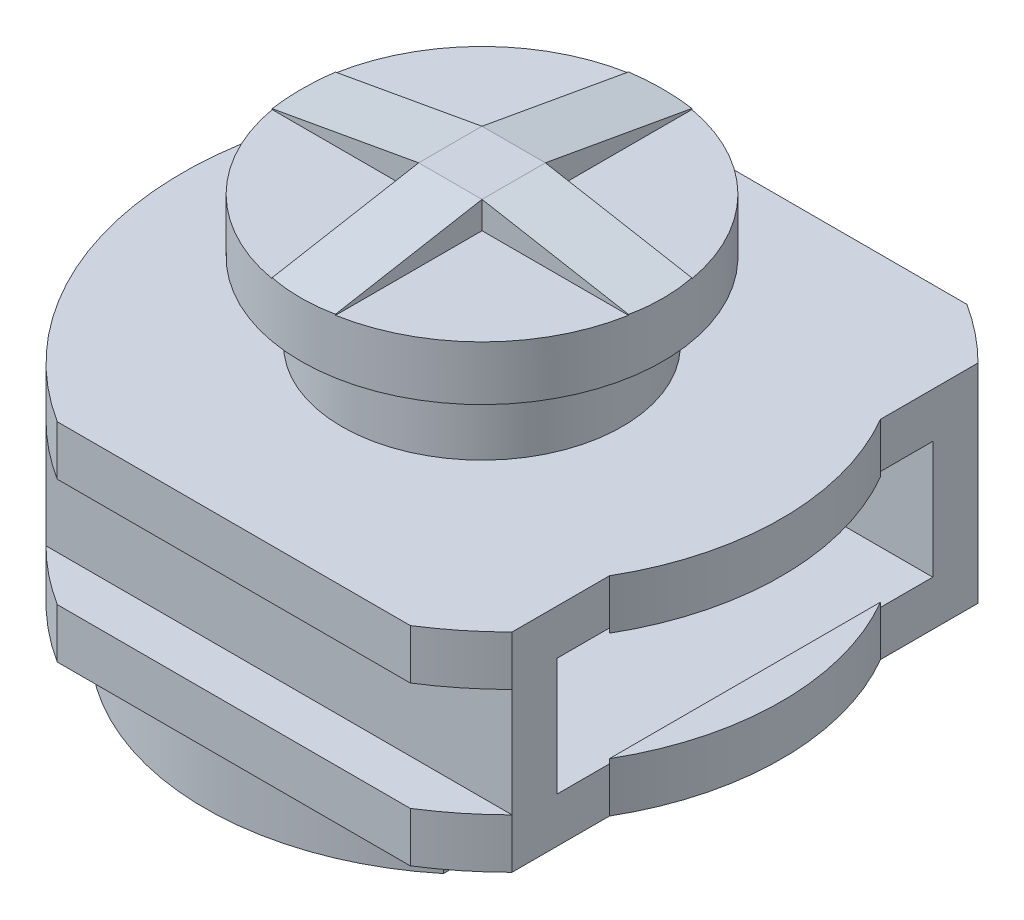
SolidWorks part; units mm, degrees
ref_plane "Front Plane" through (0, 0, 0) normal (0, 0, 1) x (1, 0, 0)
ref_plane "Top Plane" through (0, 0, 0) normal (0, 1, 0) x (1, 0, 0)
ref_plane "Right Plane" through (0, 0, 0) normal (1, 0, 0) x (0, 0, -1)
sketch "Sketch5" plane through (0, 0, 0) normal (0, 1, 0) x (1, 0, 0)
  line L1 (-5.0016, -3.942) -> (5.2984, -3.942)
  line L2 (-5.0016, -3.942) -> (-5.0016, 6.358)
  line L3 (-5.0016, 6.358) -> (5.2984, 6.358)
  line L4 (5.2984, -3.942) -> (5.2984, 6.358)
  dimension "D1" = 10.3
  dimension "D2" = 10.3
extrude "Boss-Extrude2" add sketch "Sketch5" along normal blind 4.6
sketch "Sketch6" plane through (5.2984, 0, 0) normal (1, 0, 0) x (0, 0, -1)
  line L0 (1.208, 4.6) -> (1.208, 0) construction
  line L3 (-3.942, 4.6) -> (6.358, 4.6) construction
  line L4 (-2.942, 1) -> (5.358, 1)
  line L5 (-2.942, 1) -> (-2.942, 3.6)
  line L6 (-2.942, 3.6) -> (5.358, 3.6)
  line L7 (5.358, 1) -> (5.358, 3.6)
  line L8 (-3.942, 4.6) -> (-3.942, 0) construction
  line L9 (-3.942, 0) -> (6.358, 0) construction
  line L10 (6.358, 4.6) -> (6.358, 0) construction
  dimension "D1" = 1
  dimension "D2" = 1
  dimension "D3" = 1
  dimension "D4" = 1
extrude "Cut-Extrude3" cut sketch "Sketch6" against normal blind 9.3
sketch "Sketch7" plane through (0, 4.6, 0) normal (0, 1, 0) x (1, 0, 0)
  line L0 (-5.0016, 1.208) -> (5.2984, 1.208) construction
  line L1 (-3.7532, 7.358) -> (4.05, 7.358)
  line L2 (5.2984, 6.358) -> (-5.0016, 6.358) construction
  line L3 (0.1484, 1010.6244) -> (0.1484, 8.4912) construction
  line L4 (-3.7532, -4.942) -> (4.05, -4.942)
  line L5 (0.1484, 7.358) -> (0.1484, -3.942) construction
  line L7 (5.2984, 6.358) -> (5.2984, 4.2037)
  line L8 (5.2984, -1.7877) -> (5.2984, -3.942)
  line L9 (5.2984, -1.7877) -> (5.2984, -3.942)
  arc A0 (-3.7532, 7.358) -> (-3.7532, -4.942) centre (0.1484, 1.208) ccw
  arc A1 (4.05, -4.942) -> (5.2984, -3.942) centre (0.1484, 1.208) ccw
  arc A2 (5.2984, -1.7877) -> (5.2984, 4.2037) centre (0.1484, 1.208) ccw
  arc A3 (5.2984, 6.358) -> (4.05, 7.358) centre (0.1484, 1.208) ccw
  dimension "D1" = 1
extrude "Boss-Extrude4" add sketch "Sketch7" against normal blind 1.1
ref_plane "Plane1" through (0, 2.3, 0) normal (0, 1, 0) x (1, 0, 0)
mirror "Mirror1" about plane through (0, 2.3, 0) normal (0, 1, 0) of "Boss-Extrude4", "Cut-Extrude3"
sketch "Sketch8" plane through (0, 1.1, 0) normal (0, 1, 0) x (1, 0, 0)
  line L0 (-6.3348, 4.5266) -> (-6.3348, -2.1106)
  line L1 (-5.0016, 6.358) -> (-5.0016, -3.942)
  arc A0 (-5.0016, 6.358) -> (-5.0016, -3.942) centre (0.1484, 1.208) ccw construction
  arc A1 (-6.3348, -2.1106) -> (-5.0016, -3.942) centre (0.1484, 1.208) ccw
  arc A2 (-5.0016, 6.358) -> (-6.3348, 4.5266) centre (0.1484, 1.208) ccw
  point P5 (-7.1348, 1.208)
  dimension "D1" = 0.8
extrude "Boss-Extrude5" add sketch "Sketch8" along normal up to next
sketch "Sketch9" plane through (0, 0, 0) normal (0, -1, 0) x (1, 0, 0)
  line L0 (-7.1348, -1.208) -> (6.1063, -1.208) construction
  line L1 (-0.5143, -1.208) -> (-0.5143, 4.942) construction
sketch "Sketch10" plane through (0, 0, 0) normal (0, -1, 0) x (1, 0, 0)
  line L0 (-200007.1348, -1.208) -> (200006.1063, -1.208) construction
  circle A0 centre (-0.5143, -1.208) radius 2
  dimension "D1" = 4
extrude "Cut-Extrude4" cut sketch "Sketch10" against normal through all
sketch "Sketch11" plane through (0, 4.6, 0) normal (0, 1, 0) x (1, 0, 0)
  line L0 (-200007.1348, 1.208) -> (200006.1063, 1.208) construction
  circle A0 centre (-0.5143, 1.208) radius 3.1
  circle A1 centre (-0.5143, 1.208) radius 2 construction
  circle A2 centre (-0.5143, 1.208) radius 2
  dimension "D1" = 1.1
extrude "Boss-Extrude6" add sketch "Sketch11" along normal blind 1.7
sketch "Sketch12" plane through (0, 6.3, 0) normal (0, 1, 0) x (1, 0, 0)
  line L0 (-200007.1348, 1.208) -> (200006.1063, 1.208) construction
  circle A0 centre (-0.5143, 1.208) radius 4
  point P4 (0, 0)
  dimension "D1" = 8
extrude "Boss-Extrude7" add sketch "Sketch12" along normal blind 1.2
sketch "Sketch13" plane through (0, 7.5, 0) normal (0, 1, 0) x (1, 0, 0)
  line L0 (-200007.1348, 1.208) -> (200006.1063, 1.208) construction
  line L1 (-1.2143, 5.1463) -> (-1.2143, 1.908)
  line L2 (0.1857, 5.1463) -> (0.1857, 1.908)
  line L3 (-4.4526, 1.908) -> (-1.2143, 1.908)
  line L4 (-4.4526, 0.508) -> (-1.2143, 0.508)
  line L6 (-0.5143, 200001.208) -> (-0.5143, -200004.942) construction
  line L7 (0.1857, 0.508) -> (0.1857, -2.7302)
  line L8 (-1.2143, 0.508) -> (-1.2143, -2.7302)
  line L9 (0.1857, 1.908) -> (3.424, 1.908)
  line L10 (0.1857, 0.508) -> (3.424, 0.508)
  arc A0 (-4.4526, 1.908) -> (-4.4526, 0.508) centre (-0.5143, 1.208) ccw
  arc A1 (0.1857, 5.1463) -> (-1.2143, 5.1463) centre (-0.5143, 1.208) ccw
  arc A2 (3.424, 0.508) -> (3.424, 1.908) centre (-0.5143, 1.208) ccw
  arc A3 (-1.2143, -2.7302) -> (0.1857, -2.7302) centre (-0.5143, 1.208) ccw
  dimension "D3" = 8
  dimension "D1" = 1.4
  dimension "D2" = 0.7
  dimension "D4" = 1.4
  dimension "D5" = 0.7
extrude "Boss-Extrude8" add sketch "Sketch13" along normal blind 0.6
ref_plane "Plane2" through (0, 0, -1.208) normal (0, 0, -1) x (-1, 0, 0)
sketch "Sketch14" plane through (0.1857, 0, 0) normal (1, 0, 0) x (0, 0, -1)
  line L1 (-2.8486, 7.5) -> (0.508, 8.1)
  line L7 (-2.8486, 7.5) -> (-2.8486, 8.1)
  line L8 (-2.8486, 8.1) -> (0.508, 8.1)
  line L9 (1.208, -7.3202) -> (1.208, 7.3202) construction
  line L10 (5.2647, 7.5) -> (1.908, 8.1)
  line L11 (5.2647, 7.5) -> (5.2647, 8.1)
  line L12 (5.2647, 8.1) -> (1.908, 8.1)
extrude "Cut-Extrude7" cut sketch "Sketch14" against normal through all
sketch "Sketch15" plane through (0, 0, -0.508) normal (0, 0, 1) x (1, 0, 0)
  line L0 (-0.5143, 8.1) -> (-0.5143, 6.6066) construction
  line L2 (3.5215, 8.1) -> (3.5215, 7.5)
  line L3 (-4.5501, 7.5) -> (-1.2143, 8.1)
  line L4 (-1.2143, 8.1) -> (-4.5501, 8.1)
  line L5 (-4.5501, 8.1) -> (-4.5501, 7.5)
  line L6 (0.1857, 8.1) -> (3.5215, 8.1)
  line L7 (3.5215, 7.5) -> (0.1857, 8.1)
extrude "Cut-Extrude8" cut sketch "Sketch15" against normal through all
sketch "Sketch16" plane through (0, 0, 0) normal (0, -1, 0) x (1, 0, 0)
  circle A0 centre (-0.5143, -1.208) radius 6.1184
  circle A1 centre (-0.5143, -1.208) radius 4.9184
  dimension "D1" = 1.2
extrude "Boss-Extrude9" add sketch "Sketch16" along normal blind 1.2
sketch "Sketch17" plane through (0, -1.2, 0) normal (0, -1, 0) x (1, 0, 0)
  line L0 (3.3646, 1.816) -> (3.3646, -4.2321)
  line L1 (3.3646, 1.816) -> (3.3646, 3.5237)
  line L2 (3.3646, -4.2321) -> (3.4157, -5.8974)
  circle A0 centre (-0.5143, -1.208) radius 4.9184 construction
  circle A1 centre (-0.5143, -1.208) radius 6.1184 construction
  circle A2 centre (-0.5143, -1.208) radius 6.1184 construction
  arc A3 (3.3646, 3.5237) -> (3.4157, -5.8974) centre (-0.5143, -1.208) cw
extrude "Cut-Extrude9" cut sketch "Sketch17" against normal blind 1.2
